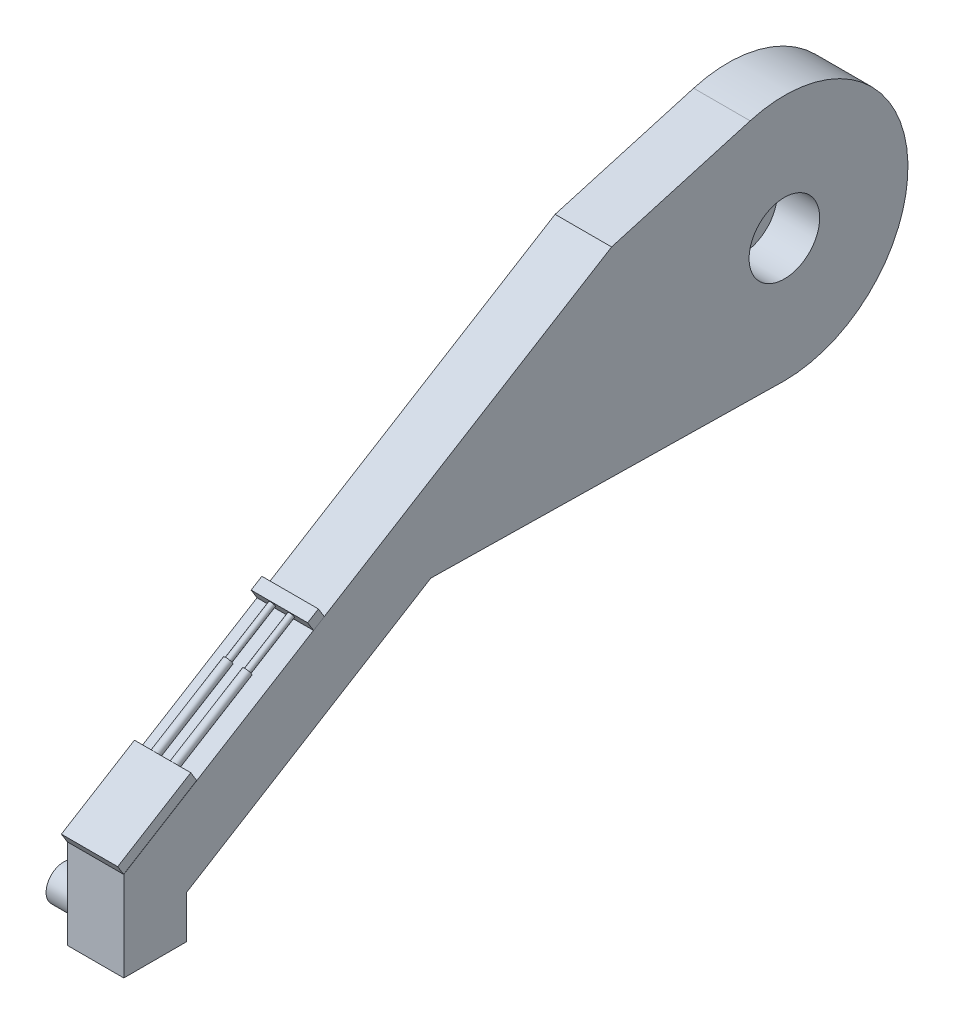
SolidWorks part; units mm, degrees
ref_plane "Front Plane" through (0, 0, 0) normal (0, 0, 1) x (1, 0, 0)
ref_plane "Top Plane" through (0, 0, 0) normal (0, 1, 0) x (1, 0, 0)
ref_plane "Right Plane" through (0, 0, 0) normal (1, 0, 0) x (0, 0, -1)
sketch "Sketch1" plane through (0, 0, 0) normal (1, 0, 0) x (0, 0, -1)
  line L0 (331.7356, 300.4528) -> (135.5568, 243.861)
  line L1 (135.5568, 243.861) -> (-555.2402, -180.3347)
  line L2 (-555.2402, -180.3347) -> (-555.2402, -307.3091)
  line L3 (-555.2402, -307.3091) -> (-466.4068, -307.3091)
  line L4 (-466.4068, -307.3091) -> (-466.4068, -246.7701)
  line L5 (-466.4068, -246.7701) -> (-120.3827, -34.2881)
  line L6 (-120.3827, -34.2881) -> (380.2402, -42.6909)
  arc A0 (380.2402, -42.6909) -> (331.7356, 300.4528) centre (380.2402, 132.3091) ccw
  dimension "D1" = 350
extrude "Boss-Extrude1" add sketch "Sketch1" along normal blind 80
sketch "Sketch2" plane through (80, 0, 0) normal (1, 0, 0) x (0, 0, -1)
  circle A0 centre (380.2402, 132.3091) radius 50
  dimension "D1" = 100
extrude "Cut-Extrude1" cut sketch "Sketch2" against normal blind 60
sketch "Sketch3" plane through (0, 0, 0) normal (-1, 0, 0) x (0, 0, 1)
  line L0 (555.2402, -307.3091) -> (466.4068, -307.3091) construction
  line L1 (555.2402, -180.3347) -> (555.2402, -307.3091) construction
  circle A0 centre (510.2402, -277.3091) radius 25
  dimension "D1" = 50
  dimension "D2" = 30
  dimension "D3" = 45
extrude "Boss-Extrude2" add sketch "Sketch3" along normal blind 50
sketch "Sketch4" plane through (0, 116.6382, 71.6237) normal (0, 0.8522, 0.5233) x (1, 0, 0)
  line L0 (80, -567.5191) -> (0, -567.5191) construction
  line L1 (79.7426, -446.1242) -> (0, -446.1242)
  line L2 (79.7426, -446.1242) -> (79.7426, -567.5191)
  line L3 (79.7426, -567.5191) -> (0, -567.5191)
  line L4 (0, -446.1242) -> (0, -567.5191)
  line L5 (79.7426, -446.1242) -> (0, -567.5191) construction
  line L6 (79.7426, -567.5191) -> (0, -446.1242) construction
  line L7 (0, 243.1242) -> (0, -567.5191) construction
  line L9 (80.0914, -234.3916) -> (0, -234.3916)
  line L10 (80.0914, -234.3916) -> (80.0914, -252.2396)
  line L11 (80.0914, -252.2396) -> (0, -252.2396)
  line L12 (0, -234.3916) -> (0, -252.2396)
  line L13 (80.0914, -234.3916) -> (0, -252.2396) construction
  line L14 (80.0914, -252.2396) -> (0, -234.3916) construction
  point P0 (39.8713, -506.8216)
  point P9 (40.0457, -243.3156)
extrude "Boss-Extrude3" add sketch "Sketch4" along normal blind 16
sketch "Sketch5" plane through (0, -131.9926, 214.9482) normal (0, -0.5233, 0.8522) x (1, 0, 0)
  line L0 (39.8713, 152.8738) -> (39.8713, 176.4976) construction
  line L1 (0, 152.8738) -> (79.7426, 152.8738) construction
  circle A0 centre (26.381, 146.4543) radius 4.2401
  circle A1 centre (53.3616, 146.4543) radius 4.2401
extrude "Boss-Extrude4" add sketch "Sketch5" along normal blind 73
sketch "Sketch6" plane through (0, -170.1923, 277.1559) normal (0, -0.5233, 0.8522) x (1, 0, 0)
  circle A0 centre (26.381, 146.4543) radius 6
  circle A1 centre (53.3616, 146.4543) radius 6
  dimension "D1" = 12
  dimension "D2" = 12
extrude "Boss-Extrude5" add sketch "Sketch6" along normal blind 130
